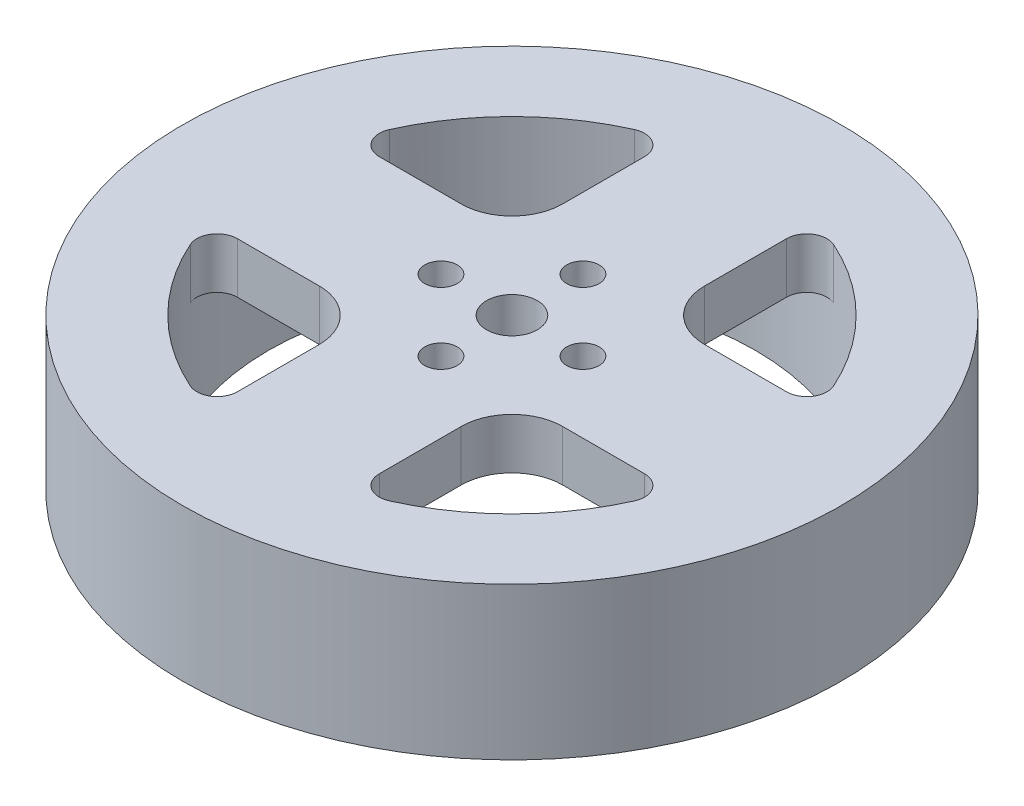
SolidWorks part; units mm, degrees
material "合金钢"
ref_plane "前视基准面" through (0, 0, 0) normal (0, 0, 1) x (1, 0, 0)
ref_plane "上视基准面" through (0, 0, 0) normal (0, 1, 0) x (1, 0, 0)
ref_plane "右视基准面" through (0, 0, 0) normal (1, 0, 0) x (0, 0, -1)
sketch "草图1" plane through (0, 0, 0) normal (0, 1, 0) x (1, 0, 0)
  circle A0 centre (0, 0) radius 32.5
  dimension "D1" = 65
extrude "凸台-拉伸1" add sketch "草图1" along normal blind 15
sketch "草图2" plane through (0, 15, 0) normal (0, 1, 0) x (1, 0, 0)
  line L0 (-32.5, 0) -> (32.5, 0) construction
  line L1 (0, 32.5) -> (0, -32.5) construction
  circle A0 centre (0, 0) radius 32.5 construction
  circle A1 centre (7, 0) radius 1.6
  circle A2 centre (0, -7) radius 1.6
  circle A3 centre (-7, 0) radius 1.6
  circle A4 centre (0, 7) radius 1.6
  dimension "D1" = 3.2
  dimension "D2" = 7
  dimension "D3" = 4
extrude "切除-拉伸1" cut sketch "草图2" against normal blind 27
sketch "草图3" plane through (0, 15, 0) normal (0, 1, 0) x (1, 0, 0)
  line L0 (0, 32.5) -> (0, -32.5) construction
  line L1 (-32.5, 0) -> (32.5, 0) construction
  line L2 (7, 22.9565) -> (7, 7)
  line L3 (7, 7) -> (22.9565, 7)
  line L4 (-7, 7) -> (-22.9565, 7)
  line L5 (-7, 22.9565) -> (-7, 7)
  line L6 (7, -7) -> (22.9565, -7)
  line L7 (7, -22.9565) -> (7, -7)
  line L8 (-7, -7) -> (-22.9565, -7)
  line L9 (-7, -22.9565) -> (-7, -7)
  arc A0 (-22.9565, -7) -> (-7, -22.9565) centre (0, 0) ccw
  circle A1 centre (0, 0) radius 32.5 construction
  arc A2 (-22.9565, 7) -> (-24, 0) centre (0, 0) ccw construction
  arc A3 (-24, 0) -> (-22.9565, -7) centre (0, 0) ccw construction
  arc A4 (7, -22.9565) -> (22.9565, -7) centre (0, 0) ccw
  arc A5 (-7, -22.9565) -> (0, -24) centre (0, 0) ccw construction
  arc A6 (0, -24) -> (7, -22.9565) centre (0, 0) ccw construction
  arc A7 (22.9565, 7) -> (7, 22.9565) centre (0, 0) ccw
  arc A8 (22.9565, -7) -> (24, 0) centre (0, 0) ccw construction
  arc A9 (24, 0) -> (22.9565, 7) centre (0, 0) ccw construction
  arc A10 (-7, 22.9565) -> (-22.9565, 7) centre (0, 0) ccw
  arc A11 (0, 24) -> (-7, 22.9565) centre (0, 0) ccw construction
  arc A12 (7, 22.9565) -> (0, 24) centre (0, 0) ccw construction
  dimension "D1" = 48
  dimension "D2" = 7
  dimension "D3" = 7
extrude "切除-拉伸2" cut sketch "草图3" against normal blind 15
fillet "圆角1" radius 5 4 edges at (-7, 7.5, 7) (7, 7.5, 7) (7, 7.5, -7) (-7, 7.5, -7)
fillet "圆角2" radius 2 8 edges at (-22.9565, 7.5, 7) (-7, 7.5, 22.9565) (7, 7.5, 22.9565) (22.9565, 7.5, 7) (-22.9565, 7.5, -7) (-7, 7.5, -22.9565) (22.9565, 7.5, -7) (7, 7.5, -22.9565)
sketch "草图4" plane through (0, 0, 0) normal (0, 1, 0) x (1, 0, 0)
  circle A0 centre (0, 0) radius 24
extrude "切除-拉伸3" cut sketch "草图4" along normal blind 10
sketch "草图5" plane through (0, 15, 0) normal (0, 1, 0) x (1, 0, 0)
  circle A0 centre (0, 0) radius 2.5
  dimension "D1" = 5
extrude "切除-拉伸4" cut sketch "草图5" against normal blind 10
